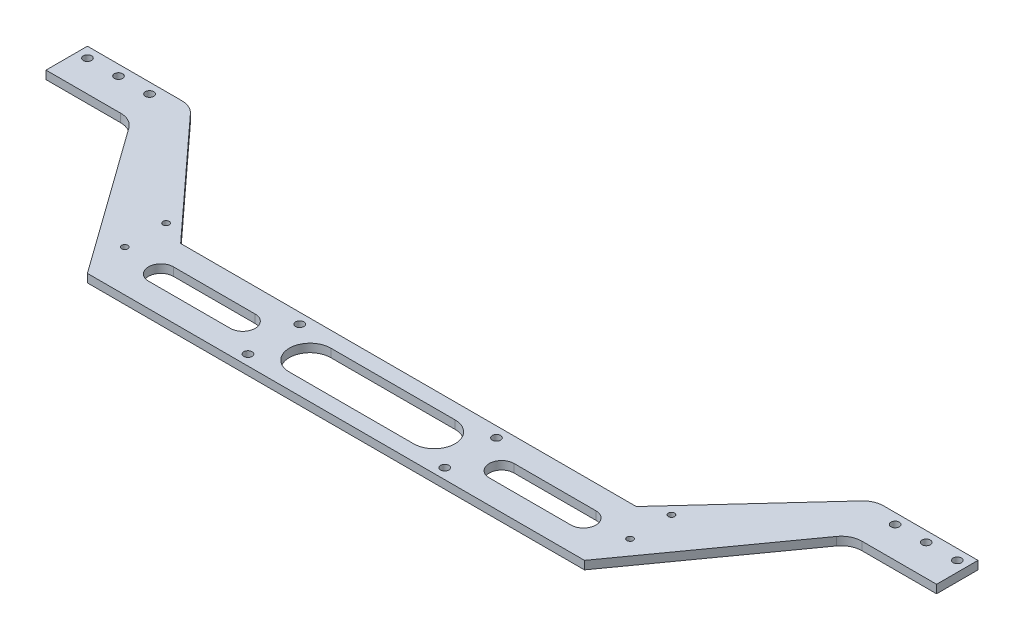
SolidWorks part; units mm, degrees
material "Thornel Mat VMA"
ref_plane "前视基准面" through (0, 0, 0) normal (0, 0, 1) x (1, 0, 0)
ref_plane "上视基准面" through (0, 0, 0) normal (0, 1, 0) x (1, 0, 0)
ref_plane "右视基准面" through (0, 0, 0) normal (1, 0, 0) x (0, 0, -1)
sketch "草图2" plane through (0, 0, 0) normal (0, 1, 0) x (1, 0, 0)
  line L1 (0, 0) -> (95, 0) construction
  line L2 (0, 0) -> (0, 25) construction
  line L3 (0, 25) -> (95, 25) construction
  line L4 (95, 0) -> (95, 25) construction
  line L5 (-72.5, -5) -> (167.5, -5)
  line L6 (-62.5, 30) -> (157.5, 30)
  line L7 (47.5, 25) -> (47.5, 0) construction
  line L9 (-72.5, -5) -> (-126.298, 70)
  line L10 (-126.298, 70) -> (-167.5, 70)
  line L11 (-167.5, 70) -> (-167.5, 90)
  line L12 (-167.5, 90) -> (-117.5, 90)
  line L13 (-117.5, 90) -> (-62.5, 30)
  line L14 (167.5, -5) -> (221.298, 70)
  line L15 (221.298, 70) -> (262.5, 70)
  line L16 (262.5, 70) -> (262.5, 90)
  line L17 (262.5, 90) -> (212.5, 90)
  line L18 (212.5, 90) -> (157.5, 30)
  line L19 (-162.5, 85) -> (-132.5, 85) construction
  line L20 (257.5, 85) -> (227.5, 85) construction
  line L21 (77.5, 12.5) -> (17.5, 12.5) construction
  line L22 (77.5, 2.5) -> (17.5, 2.5)
  line L23 (77.5, 22.5) -> (17.5, 22.5)
  circle A0 centre (0, 0) radius 2
  circle A1 centre (95, 0) radius 2
  circle A2 centre (95, 25) radius 2
  circle A3 centre (0, 25) radius 2
  circle A4 centre (-162.5, 85) radius 2
  circle A5 centre (-147.5, 85) radius 2
  circle A6 centre (-132.5, 85) radius 2
  circle A7 centre (227.5, 85) radius 2
  circle A8 centre (242.5, 85) radius 2
  circle A9 centre (257.5, 85) radius 2
  arc A10 (77.5, 2.5) -> (77.5, 22.5) centre (77.5, 12.5) ccw
  arc A11 (17.5, 22.5) -> (17.5, 2.5) centre (17.5, 12.5) ccw
  point P37 (47.5, 12.5)
  dimension "D3" = 4
  dimension "D13" = 4
  dimension "D17" = 10
  dimension "D1" = 25
  dimension "D2" = 95
  dimension "D4" = 55
  dimension "D5" = 220
  dimension "D6" = 20
  dimension "D7" = 50
  dimension "D8" = 60
  dimension "D9" = 240
  dimension "D10" = 5
  dimension "D11" = 5
  dimension "D12" = 20
  dimension "D14" = 5
  dimension "D15" = 5
  dimension "D16" = 30
  dimension "D18" = 60
extrude "凸台-拉伸1" add sketch "草图2" along normal blind 4
sketch "草图3" plane through (0, 0, 0) normal (0, -1, 0) x (1, 0, 0)
  line L0 (169.5, -35) -> (169.5, -15) construction
  line L1 (-72.5, 5) -> (167.5, 5) construction
  line L2 (47.5, 5) -> (47.5, -30) construction
  line L3 (157.5, -30) -> (-62.5, -30) construction
  line L4 (-74.5, -35) -> (-74.5, -15) construction
  circle A0 centre (169.5, -35) radius 1.5
  circle A1 centre (169.5, -15) radius 1.5
  circle A2 centre (-74.5, -15) radius 1.5
  circle A3 centre (-74.5, -35) radius 1.5
  point P6 (47.5, 5)
  dimension "D1" = 3
  dimension "D2" = 20
  dimension "D3" = 20
  dimension "D4" = 122
extrude "切除-拉伸1" cut sketch "草图3" against normal blind 10
fillet "圆角1" radius 10 4 edges at (221.298, 2, -70) (212.5, 2, -90) (-126.298, 2, -70) (-117.5, 2, -90)
sketch "草图4" plane through (0, 4, 0) normal (0, 1, 0) x (1, 0, 0)
  line L0 (-54.5, 12.5) -> (-15, 12.5) construction
  line L1 (-54.5, 18.5) -> (-15, 18.5)
  line L2 (-54.5, 6.5) -> (-15, 6.5)
  line L3 (47.5, 30) -> (47.5, -5) construction
  line L4 (157.5, 30) -> (-62.5, 30) construction
  line L5 (-72.5, -5) -> (167.5, -5) construction
  line L6 (149.5, 12.5) -> (110, 12.5) construction
  line L7 (149.5, 18.5) -> (110, 18.5)
  line L8 (149.5, 6.5) -> (110, 6.5)
  arc A0 (-54.5, 18.5) -> (-54.5, 6.5) centre (-54.5, 12.5) ccw
  arc A1 (-15, 6.5) -> (-15, 18.5) centre (-15, 12.5) ccw
  circle A2 centre (-74.5, 15) radius 1.5 construction
  circle A3 centre (0, 25) radius 2 construction
  arc A4 (149.5, 18.5) -> (149.5, 6.5) centre (149.5, 12.5) cw
  arc A5 (110, 6.5) -> (110, 18.5) centre (110, 12.5) cw
  point P2 (-34.75, 12.5)
  point P13 (47.5, 12.5)
  point P20 (129.75, 12.5)
  dimension "D1" = 6
  dimension "D2" = 20
  dimension "D3" = 15
extrude "切除-拉伸2" cut sketch "草图4" against normal through all
